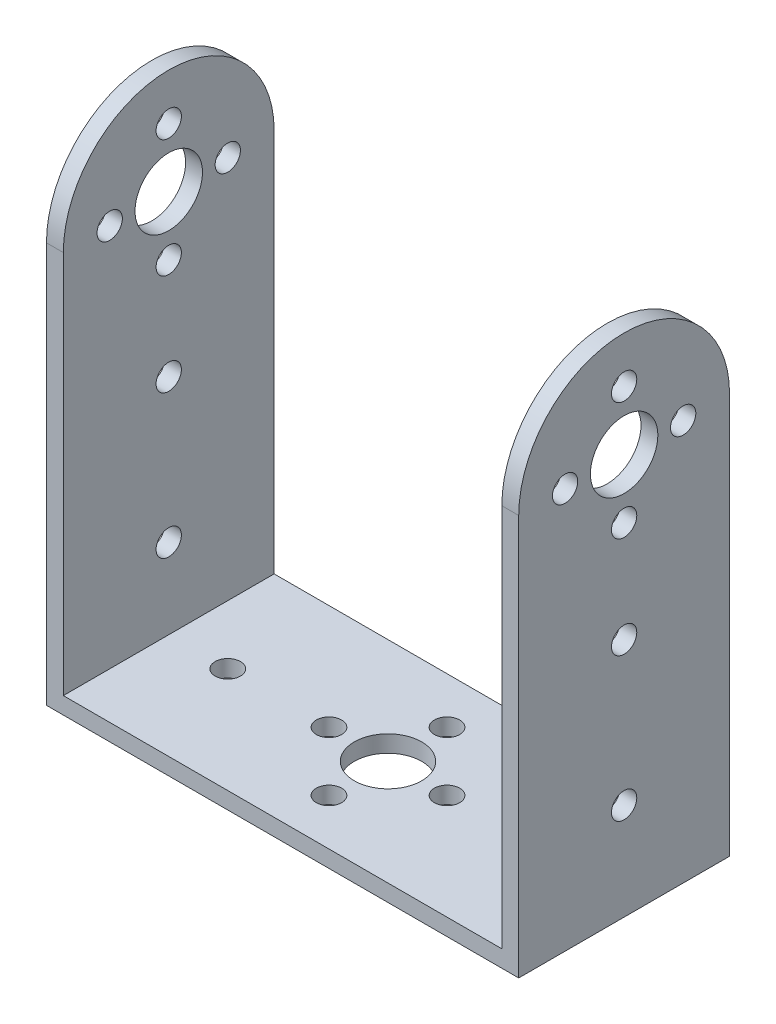
SolidWorks part; units mm, degrees
ref_plane "Front Plane" through (0, 0, 0) normal (0, 0, 1) x (1, 0, 0)
ref_plane "Top Plane" through (0, 0, 0) normal (0, 1, 0) x (1, 0, 0)
ref_plane "Right Plane" through (0, 0, 0) normal (1, 0, 0) x (0, 0, -1)
sketch "Sketch1" plane through (0, 0, 0) normal (0, 0, 1) x (1, 0, 0)
  line L0 (-26, 30) -> (-26, -28)
  line L1 (-28, -30) -> (28, -30)
  line L2 (-28, -30) -> (-28, 30)
  line L3 (-28, 30) -> (-26, 30)
  line L4 (28, -30) -> (28, 30)
  line L5 (-28, -30) -> (28, 30) construction
  line L6 (-28, 30) -> (28, -30) construction
  line L7 (-26, -28) -> (26, -28)
  line L8 (26, -28) -> (26, 30)
  line L9 (26, 30) -> (28, 30)
  point P0 (0, 0)
  dimension "D1" = 2
  dimension "D2" = 2
  dimension "D3" = 56
  dimension "D4" = 60
extrude "Boss-Extrude1" add sketch "Sketch1" along normal blind 25
sketch "Sketch2" plane through (28, 0, 0) normal (1, 0, 0) x (0, 0, -1)
  line L0 (-25, -30) -> (-25, 30) construction
  line L1 (0, -30) -> (0, 30) construction
  line L2 (-25, 30) -> (0, 30) construction
  line L3 (-25, 17.5) -> (-25, 33.6556)
  line L4 (-25, 33.6556) -> (0, 33.6556)
  line L5 (0, 33.6556) -> (0, 17.5)
  line L6 (-12.5, 17.5) -> (-12.5, -30) construction
  line L7 (-25, -30) -> (0, -30) construction
  line L8 (-12.5, 17.5) -> (-19.5, 17.5) construction
  arc A0 (0, 17.5) -> (-25, 17.5) centre (-12.5, 17.5) ccw
  circle A1 centre (-12.5, 17.5) radius 4
  circle A2 centre (-19.5, 17.5) radius 1.5
  circle A3 centre (-12.5, -1.5) radius 1.5
  circle A4 centre (-12.5, -18.5) radius 1.5
  circle A5 centre (-12.5, 24.5) radius 1.5
  circle A6 centre (-5.5, 17.5) radius 1.5
  circle A7 centre (-12.5, 10.5) radius 1.5
  point P32 (-12.5, 17.5)
  dimension "D2" = 3
  dimension "D3" = 8
  dimension "D4" = 7
  dimension "D5" = 12
  dimension "D6" = 17
  dimension "D1" = 4
extrude "Cut-Extrude1" cut sketch "Sketch2" against normal through all
sketch "Sketch3" plane through (0, -30, 0) normal (0, -1, 0) x (1, 0, 0)
  line L0 (0, 0) -> (0, 25) construction
  line L1 (-28, 25) -> (28, 25) construction
  line L2 (-28, 12.5) -> (28, 12.5) construction
  line L3 (-28, 25) -> (-28, 0) construction
  line L4 (28, 25) -> (28, 0) construction
  circle A0 centre (0, 12.5) radius 4
  circle A1 centre (-7, 12.5) radius 1.5
  circle A2 centre (0, 19.5) radius 1.5
  circle A3 centre (7, 12.5) radius 1.5
  circle A4 centre (0, 5.5) radius 1.5
  circle A5 centre (-19, 12.5) radius 1.5
  circle A6 centre (19, 12.5) radius 1.5
  point P24 (0, 12.5)
  dimension "D1" = 7
  dimension "D2" = 3
  dimension "D3" = 8
  dimension "D5" = 12
  dimension "D6" = 12
  dimension "D4" = 4
extrude "Cut-Extrude2" cut sketch "Sketch3" against normal through all
